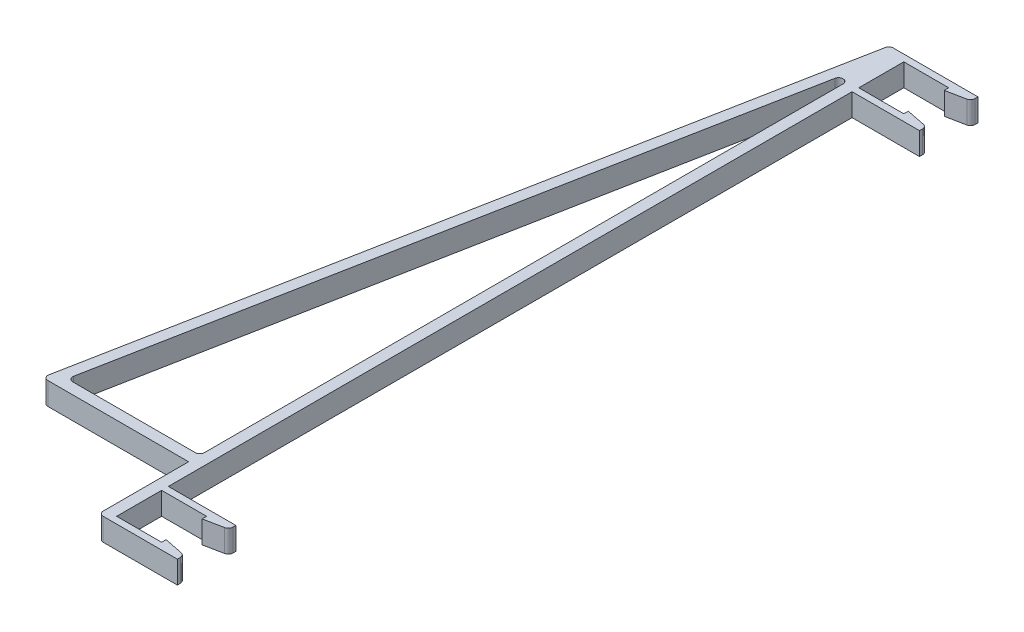
SolidWorks part; units mm, degrees
ref_plane "前视基准面" through (0, 0, 0) normal (0, 0, 1) x (1, 0, 0)
ref_plane "上视基准面" through (0, 0, 0) normal (0, 1, 0) x (1, 0, 0)
ref_plane "右视基准面" through (0, 0, 0) normal (1, 0, 0) x (0, 0, -1)
sketch "草图1" plane through (0, 0, 0) normal (0, 1, 0) x (1, 0, 0)
  line L0 (0, 0) -> (-180.8333, 0) construction
  line L1 (-15, -178) -> (15, -178)
  line L2 (-15, -178) -> (-15, 178)
  line L3 (-15, 178) -> (15, 178)
  line L4 (15, -178) -> (15, 178)
  line L5 (-15, -178) -> (15, 178) construction
  line L6 (-15, 178) -> (15, -178) construction
  line L7 (15, 175) -> (-15, 175)
  line L8 (15, 175) -> (15, -175)
  line L9 (15, -175) -> (-15, -175)
  line L10 (-15, 175) -> (-15, -175)
  line L11 (15, 175) -> (5, 173)
  line L12 (5, 173) -> (5, 175)
  line L13 (5, 175) -> (15, 175)
  line L14 (5, -175) -> (15, -175)
  line L15 (5, -173) -> (5, -175)
  line L16 (15, -175) -> (5, -173)
  line L17 (-15, -152) -> (15, -152)
  line L18 (-15, 178) -> (-20, 178)
  line L19 (-15, 178) -> (-15, -178)
  line L20 (-15, -178) -> (-20, -178)
  line L21 (-20, 178) -> (-20, -178)
  line L22 (-15, 155) -> (15, 155)
  line L23 (-15, 155) -> (-15, 152)
  line L24 (-15, 152) -> (15, 152)
  line L25 (15, 155) -> (15, 152)
  line L26 (15, -155) -> (15, -152)
  line L27 (-15, -155) -> (15, -155)
  line L28 (-15, -155) -> (-15, -152)
  line L29 (15, 155) -> (5, 157)
  line L30 (5, 157) -> (5, 155)
  line L31 (5, 155) -> (15, 155)
  line L32 (-20, -138) -> (-85, -138)
  line L33 (-15, 178) -> (15, 178)
  line L34 (-15, 178) -> (-15, 175)
  line L35 (-15, 175) -> (15, 175)
  line L36 (15, 178) -> (15, 175)
  line L37 (15, -178) -> (-15, -178)
  line L38 (15, -178) -> (15, -175)
  line L39 (15, -175) -> (-15, -175)
  line L40 (-15, -178) -> (-15, -175)
  line L41 (-20, -178) -> (-93.6817, -178) construction
  line L42 (-20, -178) -> (-20, -138) construction
  line L43 (-20, -138) -> (-93.6817, -138) construction
  line L44 (-93.6817, -178) -> (-93.6817, -138) construction
  line L45 (-85, -138) -> (-24.3233, 178)
  line L46 (-24.3233, 178) -> (-20, 178)
  line L47 (-20, -138) -> (-20, 178)
  line L48 (-20, 174) -> (-20, -133)
  line L49 (-20, -133) -> (-78.9486, -133)
  line L50 (-78.9486, -133) -> (-20, 174)
  line L51 (5, -155) -> (15, -155)
  line L52 (5, -157) -> (5, -155)
  line L53 (15, -155) -> (5, -157)
  point P0 (0, 0)
  dimension "D1" = 356
  dimension "D2" = 350
  dimension "D3" = 30
  dimension "D4" = 20
  dimension "D5" = 5
  dimension "D6" = 20
  dimension "D7" = 3
  dimension "D8" = 2
  dimension "D9" = 2
  dimension "D10" = 40
  dimension "D11" = 70
  dimension "D12" = 5
  dimension "D13" = 5
  dimension "D14" = 0
  dimension "D15" = 4
extrude "凸台-拉伸1" add sketch "草图1" along normal blind 10 contours L49 L50 L21 L46 L45 L32 | L18 L21 L47 L20 L2 L19 L10 | L4 L9 L2 L1 | L53 L27 L52 | L9 L16 L15 | L7 L4 L3 L2 | L19 L24 L4 L22 | L29 L30 L22 | L12 L11 L7
fillet "圆角1" radius 2 10 edges at (-24.3233, 5, -178) (-85, 5, 138) (-20, 5, 178) (15, 5, 175) (15, 5, -155) (15, 5, -175) (-20, 5, -174) (-20, 5, 133) (-78.9486, 5, 133) (15, 5, 155)
